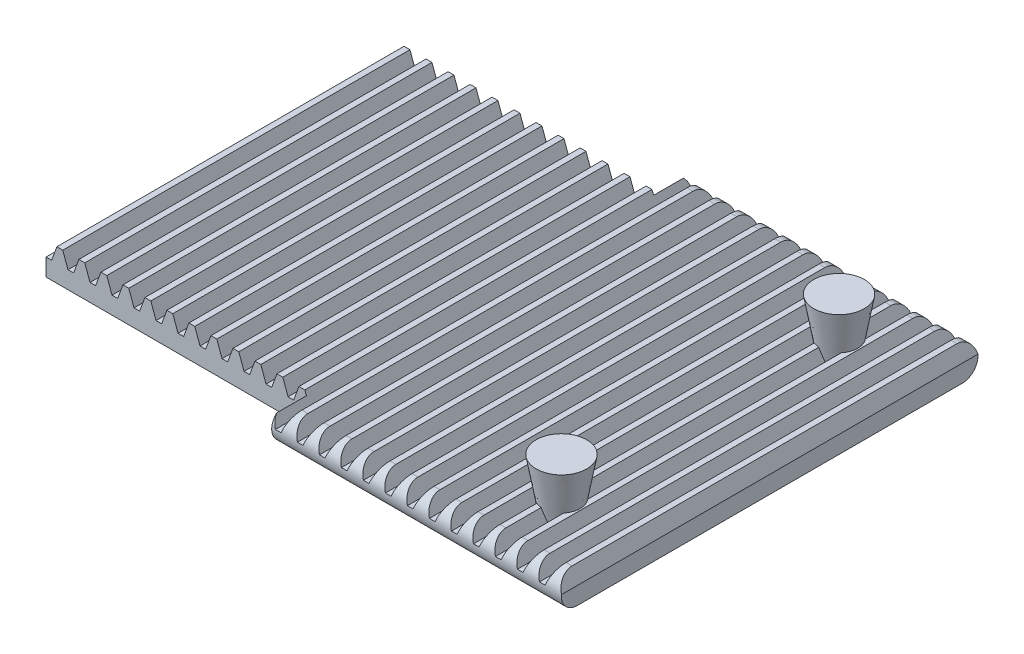
SolidWorks part; units mm, degrees
ref_plane "Front Plane" through (0, 0, 0) normal (0, 0, 1) x (1, 0, 0)
ref_plane "Top Plane" through (0, 0, 0) normal (0, 1, 0) x (1, 0, 0)
ref_plane "Right Plane" through (0, 0, 0) normal (1, 0, 0) x (0, 0, -1)
sketch "Sketch4" plane through (-229.7823, -228.5123, 0) normal (0, 0, 1) x (0, 1, 0)
  line L0 (-0.8477, -8.5519) -> (0.8074, -7.9495)
  line L1 (0.8074, -7.9495) -> (0.8074, -7.269)
  line L2 (0.8074, -7.269) -> (-0.8477, -6.6666)
  line L3 (-0.8477, -6.6666) -> (-0.8477, -6.0168)
  line L4 (-0.8477, -6.0168) -> (0.8074, -5.4144)
  line L5 (0.8074, -5.4144) -> (0.8074, -4.7339)
  line L6 (0.8074, -4.7339) -> (-0.8477, -4.1315)
  line L7 (-0.8477, -4.1315) -> (-0.8477, -3.4817)
  line L8 (-0.8477, -3.4817) -> (0.8074, -2.8792)
  line L9 (0.8074, -2.8792) -> (0.8074, -2.1988)
  line L10 (0.8074, -2.1988) -> (-0.8477, -1.5963)
  line L11 (-0.8477, -1.5963) -> (-0.8477, -0.9465)
  line L12 (-0.8477, -0.9465) -> (0.8074, -0.3441)
  line L13 (0.8074, -0.3441) -> (0.8074, 0.3364)
  line L14 (0.8074, 0.3364) -> (-0.8477, 0.9388)
  line L15 (-0.8477, 0.9388) -> (-0.8477, 1.5886)
  line L16 (-0.8477, 1.5886) -> (0.8074, 2.191)
  line L17 (0.8074, 2.191) -> (0.8074, 2.8715)
  line L18 (0.8074, 2.8715) -> (-0.8477, 3.4739)
  line L19 (-0.8477, 3.4739) -> (-0.8477, 4.1238)
  line L20 (-0.8477, 4.1238) -> (0.8074, 4.7262)
  line L21 (0.8074, 4.7262) -> (0.8074, 5.4067)
  line L22 (0.8074, 5.4067) -> (-0.8477, 6.0091)
  line L23 (-0.8477, 6.0091) -> (-0.8477, 6.6589)
  line L24 (-0.8477, 6.6589) -> (0.8074, 7.2613)
  line L25 (0.8074, 7.2613) -> (0.8074, 7.9418)
  line L26 (0.8074, 7.9418) -> (-0.8477, 8.5442)
  line L27 (-0.8477, 8.5442) -> (-0.8477, 9.1941)
  line L28 (-0.8477, 9.1941) -> (0.8074, 9.7965)
  line L29 (0.8074, 9.7965) -> (0.8074, 10.477)
  line L30 (0.8074, 10.477) -> (-0.8477, 11.0794)
  line L31 (-0.8477, 11.0794) -> (-0.8477, 11.7292)
  line L32 (-0.8477, 11.7292) -> (0.8074, 12.3316)
  line L33 (0.8074, 12.3316) -> (0.8074, 13.0121)
  line L34 (0.8074, 13.0121) -> (-0.8477, 13.6145)
  line L35 (-0.8477, 13.6145) -> (-0.8477, 14.2643)
  line L36 (-0.8477, 14.2643) -> (0.8074, 14.8667)
  line L37 (0.8074, 14.8667) -> (0.8074, 15.5472)
  line L38 (0.8074, 15.5472) -> (-0.8477, 16.1497)
  line L39 (-0.8477, 16.1497) -> (-0.8477, 16.7995)
  line L40 (-0.8477, 16.7995) -> (0.8074, 17.4019)
  line L41 (0.8074, 17.4019) -> (0.8074, 18.0824)
  line L42 (0.8074, 18.0824) -> (-0.8477, 18.6848)
  line L43 (-0.8477, 18.6848) -> (-0.8477, 19.3346)
  line L44 (-0.8477, 19.3346) -> (0.8074, 19.937)
  line L45 (0.8074, 19.937) -> (0.8074, 20.6175)
  line L46 (0.8074, 20.6175) -> (-0.8477, 21.2199)
  line L47 (-0.8477, 21.2199) -> (-0.8477, 21.8698)
  line L48 (-0.8477, 21.8698) -> (0.8074, 22.4722)
  line L49 (0.8074, 22.4722) -> (0.8074, 23.1527)
  line L50 (0.8074, 23.1527) -> (-0.8477, 23.7551)
  line L51 (-0.8477, 23.7551) -> (-0.8477, 24.4049)
  line L52 (-0.8477, 24.4049) -> (0.8074, 25.0073)
  line L53 (0.8074, 25.0073) -> (0.8074, 25.6878)
  line L54 (0.8074, 25.6878) -> (-0.8477, 26.2902)
  line L55 (-0.8477, 26.2902) -> (-0.8477, 26.94)
  line L56 (-0.8477, 26.94) -> (0.8074, 27.5425)
  line L57 (0.8074, 27.5425) -> (0.8074, 28.223)
  line L58 (0.8074, 28.223) -> (-0.8477, 28.8254)
  line L59 (-0.8477, 28.8254) -> (-0.8477, 29.4752)
  line L60 (-0.8477, 29.4752) -> (0.8074, 30.0776)
  line L61 (0.8074, 30.0776) -> (0.8074, 30.7581)
  line L62 (0.8074, 30.7581) -> (-0.8477, 31.3605)
  line L63 (-0.8477, 31.3605) -> (-0.8477, 32.0103)
  line L64 (-0.8477, 32.0103) -> (0.8074, 32.6127)
  line L65 (0.8074, 32.6127) -> (0.8074, 33.2932)
  line L66 (0.8074, 33.2932) -> (-0.8477, 33.8956)
  line L67 (-0.8477, 33.8956) -> (-0.8477, 34.5455)
  line L68 (-0.8477, 34.5455) -> (0.8074, 35.1479)
  line L69 (0.8074, 35.1479) -> (0.8074, 35.8284)
  line L70 (0.8074, 35.8284) -> (-0.8477, 36.4308)
  line L71 (-0.8477, 36.4308) -> (-0.8477, 37.0806)
  line L72 (-0.8477, 37.0806) -> (0.8074, 37.683)
  line L73 (0.8074, 37.683) -> (0.8074, 38.3635)
  line L74 (0.8074, 38.3635) -> (-0.8477, 38.9659)
  line L75 (-0.8477, 38.9659) -> (-0.8477, 39.6158)
  line L76 (-0.8477, 39.6158) -> (0.8074, 40.2182)
  line L77 (0.8074, 40.2182) -> (0.8074, 40.8987)
  line L78 (0.8074, 40.8987) -> (-0.8477, 41.5011)
  line L79 (-0.8477, 41.5011) -> (-0.8477, 42.1509)
  line L80 (-0.8477, -8.5519) -> (-2.8477, -8.5519)
  line L81 (-2.8477, 54.8266) -> (-2.8477, -8.5519)
  line L82 (-0.8477, 54.8266) -> (-2.8477, 54.8266)
  line L83 (-0.8477, 42.1509) -> (0.8074, 42.7533)
  line L84 (0.8074, 42.7533) -> (0.8074, 43.4338)
  line L85 (0.8074, 43.4338) -> (-0.8477, 44.0362)
  line L86 (-0.8477, 44.0362) -> (-0.8477, 44.686)
  line L87 (-0.8477, 44.686) -> (0.8074, 45.2884)
  line L88 (0.8074, 45.2884) -> (0.8074, 45.9689)
  line L89 (0.8074, 45.9689) -> (-0.8477, 46.5714)
  line L90 (-0.8477, 46.5714) -> (-0.8477, 47.2212)
  line L91 (-0.8477, 47.2212) -> (0.8074, 47.8236)
  line L92 (0.8074, 47.8236) -> (0.8074, 48.5041)
  line L93 (0.8074, 48.5041) -> (-0.8477, 49.1065)
  line L94 (-0.8477, 49.1065) -> (-0.8477, 49.7563)
  line L95 (-0.8477, 49.7563) -> (0.8074, 50.3587)
  line L96 (0.8074, 50.3587) -> (0.8074, 51.0392)
  line L97 (0.8074, 51.0392) -> (-0.8477, 51.6416)
  line L98 (-0.8477, 51.6416) -> (-0.8477, 52.2915)
  line L99 (-0.8477, 52.2915) -> (0.8074, 52.8939)
  line L100 (0.8074, 52.8939) -> (0.8074, 53.5744)
  line L101 (0.8074, 53.5744) -> (-0.8477, 54.1768)
  line L102 (-0.8477, 54.1768) -> (-0.8477, 54.8266)
  dimension "D2" = 2
  dimension "D1" = 25
extrude "Boss-Extrude1" add sketch "Sketch4" along normal mid plane 48
sketch "Sketch6" plane through (0, -231.3601, 0) normal (0, -1, 0) x (1, 0, 0)
  line L9 (2.0103, 0) -> (-2.0103, 0) construction
  line L10 (-284.6089, -24) -> (-254.6089, -24)
  line L11 (-284.6089, -24) -> (-284.6089, -20)
  line L12 (-284.6089, -20) -> (-254.6089, -20)
  line L13 (-254.6089, -24) -> (-254.6089, -20)
  line L14 (-254.6089, 24) -> (-254.6089, 20)
  line L15 (-284.6089, 20) -> (-254.6089, 20)
  line L16 (-284.6089, 24) -> (-284.6089, 20)
  line L17 (-284.6089, 24) -> (-254.6089, 24)
  dimension "D1" = 4
  dimension "D2" = 30
extrude "Cut-Extrude2" cut sketch "Sketch6" against normal through all
sketch "Sketch5" plane through (-221.2304, 0, 0) normal (1, 0, 0) x (0, 0, -1)
  line L3 (-24, -227.705) -> (24, -227.705) construction
  line L4 (-24, -231.3601) -> (-24, -229.3601) construction
  line L5 (-22.1724, -227.705) -> (-22.1724, -227.205)
  line L6 (-22.1724, -227.205) -> (-24.6724, -227.205)
  line L7 (-24.6724, -227.205) -> (-24.6724, -231.8601)
  line L8 (-24.6724, -231.8601) -> (-22.1724, -231.8601)
  line L9 (-22.1724, -231.8601) -> (-22.1724, -231.3601)
  line L10 (0, 2.0103) -> (0, -2.0103) construction
  line L11 (22.1724, -231.8601) -> (22.1724, -231.3601)
  line L12 (24.6724, -231.8601) -> (22.1724, -231.8601)
  line L13 (24.6724, -227.205) -> (24.6724, -231.8601)
  line L14 (22.1724, -227.205) -> (24.6724, -227.205)
  line L15 (22.1724, -227.705) -> (22.1724, -227.205)
  line L16 (-24, -231.3601) -> (24, -231.3601) construction
  arc A1 (-22.1724, -227.705) -> (-22.1724, -231.3601) centre (-22.1724, -229.5325) ccw
  arc A2 (22.1724, -227.705) -> (22.1724, -231.3601) centre (22.1724, -229.5325) cw
  dimension "D1" = 2.5
  dimension "D2" = 0.5
extrude "Cut-Extrude1" cut sketch "Sketch5" against normal through all
sketch "Sketch7" plane through (0, -231.3601, 0) normal (0, -1, 0) x (1, 0, 0)
  line L0 (2.0103, 0) -> (-2.0103, 0) construction
  circle A0 centre (-229.2304, -15.9918) radius 1.5
  circle A1 centre (-229.2304, 15.9918) radius 1.5
  dimension "D1" = 3
  dimension "D2" = 8
  dimension "D3" = 8
extrude "Boss-Extrude2" add sketch "Sketch7" against normal blind 8 draft 10 draft outward yes
